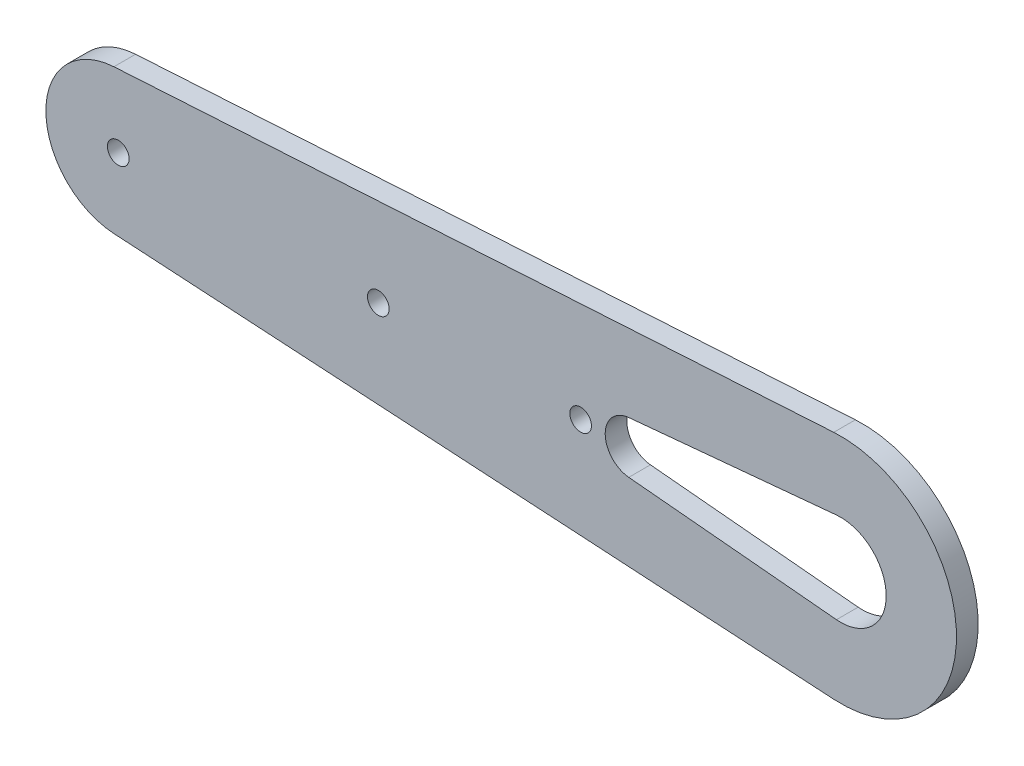
SolidWorks part; units mm, degrees
ref_plane "Front Plane" through (0, 0, 0) normal (0, 0, 1) x (1, 0, 0)
ref_plane "Top Plane" through (0, 0, 0) normal (0, 1, 0) x (1, 0, 0)
ref_plane "Right Plane" through (0, 0, 0) normal (1, 0, 0) x (0, 0, -1)
sketch "Sketch1" plane through (0, 0, 0) normal (0, 0, 1) x (1, 0, 0)
  line L0 (-52.5102, -2.3133) -> (47.1285, 3.6867)
  line L1 (47.1285, -28.3133) -> (-52.5102, -22.3133)
  arc A0 (47.1285, 3.6867) -> (47.1285, -28.3133) centre (48.092, -12.3133) cw
  arc A1 (-52.5102, -22.3133) -> (-52.5102, -2.3133) centre (-51.908, -12.3133) cw
  point P6 (-4.8962, -33.0222)
  point P7 (0, 0)
  point P8 (86.1732, 12.6757)
  point P9 (-51.1382, -1.4689)
  point P10 (41.0193, 5.277)
  dimension "D1" = 100
  dimension "D2" = 20
  dimension "D3" = 32
extrude "Boss-Extrude1" add sketch "Sketch1" along normal blind 3
sketch "Sketch2" plane through (0, 0, 3) normal (0, 0, 1) x (1, 0, 0)
  line L0 (18.7568, -8.7289) -> (47.5054, -6.0406)
  line L1 (47.5054, -18.5859) -> (18.7568, -15.8976)
  arc A0 (47.5054, -6.0406) -> (47.5054, -18.5859) centre (48.092, -12.3133) cw
  arc A1 (18.7568, -15.8976) -> (18.7568, -8.7289) centre (19.092, -12.3133) cw
  arc A2 (47.1285, -28.3133) -> (47.1285, 3.6867) centre (48.092, -12.3133) ccw construction
  circle A4 centre (12.092, -12.3133) radius 1.5
  circle A5 centre (-15.908, -12.3133) radius 1.5
  circle A6 centre (-51.908, -12.3133) radius 1.5
  arc A7 (-52.5102, -2.3133) -> (-52.5102, -22.3133) centre (-51.908, -12.3133) ccw construction
  point P14 (15.492, -12.3133)
  point P15 (54.392, -12.3133)
  point P20 (0, 0)
  dimension "D1" = 6.3
  dimension "D3" = 3.6
  dimension "D4" = 36
  dimension "D2" = 38.9
  dimension "D5" = 36
extrude "Cut-Extrude1" cut sketch "Sketch2" against normal blind 3
